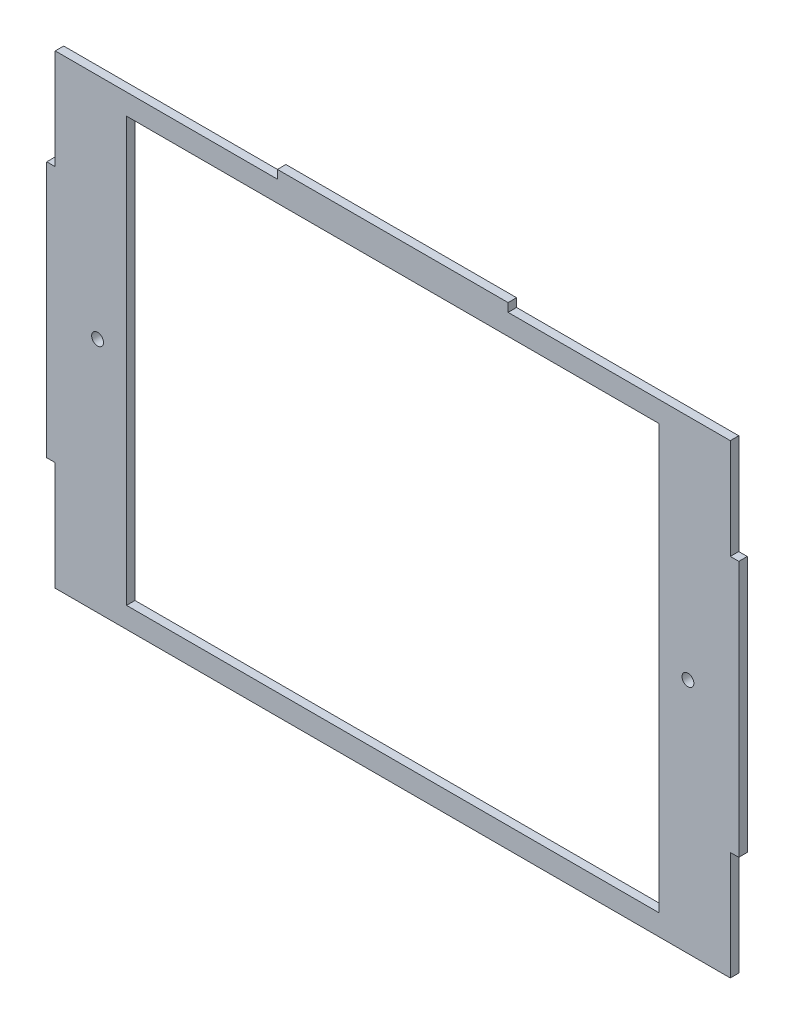
SolidWorks part; units mm, degrees
ref_plane "Front Plane" through (0, 0, 0) normal (0, 0, 1) x (1, 0, 0)
ref_plane "Top Plane" through (0, 0, 0) normal (0, 1, 0) x (1, 0, 0)
ref_plane "Right Plane" through (0, 0, 0) normal (1, 0, 0) x (0, 0, -1)
sketch "Sketch1" plane through (0, 0, 0) normal (0, 0, 1) x (1, 0, 0)
  line L1 (0, 0) -> (490, 0)
  line L2 (0, 0) -> (0, 335.5)
  line L3 (0, 335.5) -> (490, 335.5)
  line L4 (490, 0) -> (490, 335.5)
  dimension "D1" = 490
  dimension "D2" = 335.5
extrude "Boss-Extrude1" add sketch "Sketch1" along normal blind 6
sketch "Sketch3" plane through (0, 0, 6) normal (0, 0, 1) x (1, 0, 0)
  line L0 (0, 335.5) -> (0, 0) construction
  line L1 (56.5, 14.75) -> (433.5, 14.75)
  line L2 (56.5, 14.75) -> (56.5, 314.75)
  line L3 (56.5, 314.75) -> (433.5, 314.75)
  line L4 (433.5, 14.75) -> (433.5, 314.75)
  line L5 (490, 335.5) -> (0, 335.5) construction
  dimension "D1" = 377
  dimension "D2" = 300
  dimension "D3" = 56.5
  dimension "D4" = 20.75
sketch "Sketch5" plane through (0, 0, 6) normal (0, 0, 1) x (1, 0, 0)
  line L1 (0, 335.5) -> (6, 335.5)
  line L2 (0, 335.5) -> (0, 258.5)
  line L3 (0, 258.5) -> (6, 258.5)
  line L4 (6, 335.5) -> (6, 258.5)
  line L5 (0, 0) -> (6, 0)
  line L6 (0, 0) -> (0, 77)
  line L7 (0, 77) -> (6, 77)
  line L8 (6, 0) -> (6, 77)
  line L9 (490, 335.5) -> (484, 335.5)
  line L10 (490, 335.5) -> (490, 258.5)
  line L11 (490, 258.5) -> (484, 258.5)
  line L12 (484, 335.5) -> (484, 258.5)
  line L13 (490, 0) -> (484, 0)
  line L14 (490, 0) -> (490, 77)
  line L15 (490, 77) -> (484, 77)
  line L16 (484, 0) -> (484, 77)
  dimension "D1" = 6
  dimension "D2" = 77
extrude "Cut-Extrude2" cut sketch "Sketch5" against normal through all
extrude "Cut-Extrude3" cut sketch "Sketch3" against normal through all
sketch "Sketch6" plane through (0, 0, 6) normal (0, 0, 1) x (1, 0, 0)
  line L1 (484, 335.5) -> (326.6667, 335.5)
  line L2 (484, 335.5) -> (484, 329.5)
  line L3 (484, 329.5) -> (326.6667, 329.5)
  line L4 (326.6667, 335.5) -> (326.6667, 329.5)
  line L5 (6, 335.5) -> (163.3333, 335.5)
  line L6 (6, 335.5) -> (6, 329.5)
  line L7 (6, 329.5) -> (163.3333, 329.5)
  line L8 (163.3333, 335.5) -> (163.3333, 329.5)
  point P10 (326.6667, 332.5)
  dimension "D1" = 6
  dimension "D2" = 163.3333
extrude "Cut-Extrude4" cut sketch "Sketch6" against normal through all
hole_wizard "M8 Clearance Slot1" positions "Sketch7" profile "Sketch8" size "M8" standard "ANSI Metric" slot yes end condition through all
sketch "Sketch7" plane through (0, 0, 6) normal (0, 0, 1) x (1, 0, 0)
  line L0 (0, 258.5) -> (0, 77) construction
  line L1 (490, 77) -> (490, 258.5) construction
  line L2 (484, 258.5) -> (490, 258.5) construction
  line L3 (0, 258.5) -> (6, 258.5) construction
  point P0 (36, 167.75)
  point P2 (454, 167.75)
  dimension "D1" = 36
  dimension "D2" = 36
  dimension "D3" = 90.75
  dimension "D4" = 90.75
sketch "Sketch8" plane through (36, 167.75, 6) normal (1, 0, 0) x (0, -1, 0)
  line L0 (0, 0) -> (0, 6)
  line L1 (0, 6) -> (4.2, 6)
  line L2 (4.2, 6) -> (4.2, 0)
  line L5 (4.2, 0) -> (0, 0)
  line L11 (0, -6.35) -> (0, 107.95) construction
  dimension "Thru Hole Dia." = 8.4
  dimension "Thru Hole Depth" = 6
